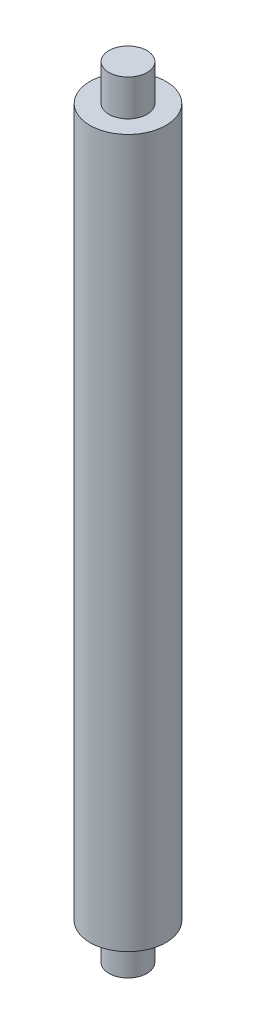
SolidWorks part; units mm, degrees
material "6061 Alloy"
ref_plane "Front Plane" through (0, 0, 0) normal (0, 0, 1) x (1, 0, 0)
ref_plane "Top Plane" through (0, 0, 0) normal (0, 1, 0) x (1, 0, 0)
ref_plane "Right Plane" through (0, 0, 0) normal (1, 0, 0) x (0, 0, -1)
sketch "Sketch1" plane through (0, 0, 0) normal (0, 1, 0) x (1, 0, 0)
  circle A0 centre (0, 0) radius 5
  dimension "D1" = 10
extrude "Boss-Extrude1" add sketch "Sketch1" along normal blind 92.964
sketch "Sketch2" plane through (0, 92.964, 0) normal (0, 1, 0) x (1, 0, 0)
  circle A0 centre (0, 0) radius 2.5
  dimension "D1" = 5
extrude "Boss-Extrude2" add sketch "Sketch2" along normal blind 4.7625 contours A0
sketch "Sketch3" plane through (0, 0, 0) normal (0, -1, 0) x (1, 0, 0)
  circle A0 centre (0, 0) radius 2.5
  dimension "D1" = 5
extrude "Boss-Extrude3" add sketch "Sketch3" along normal blind 4.7625
